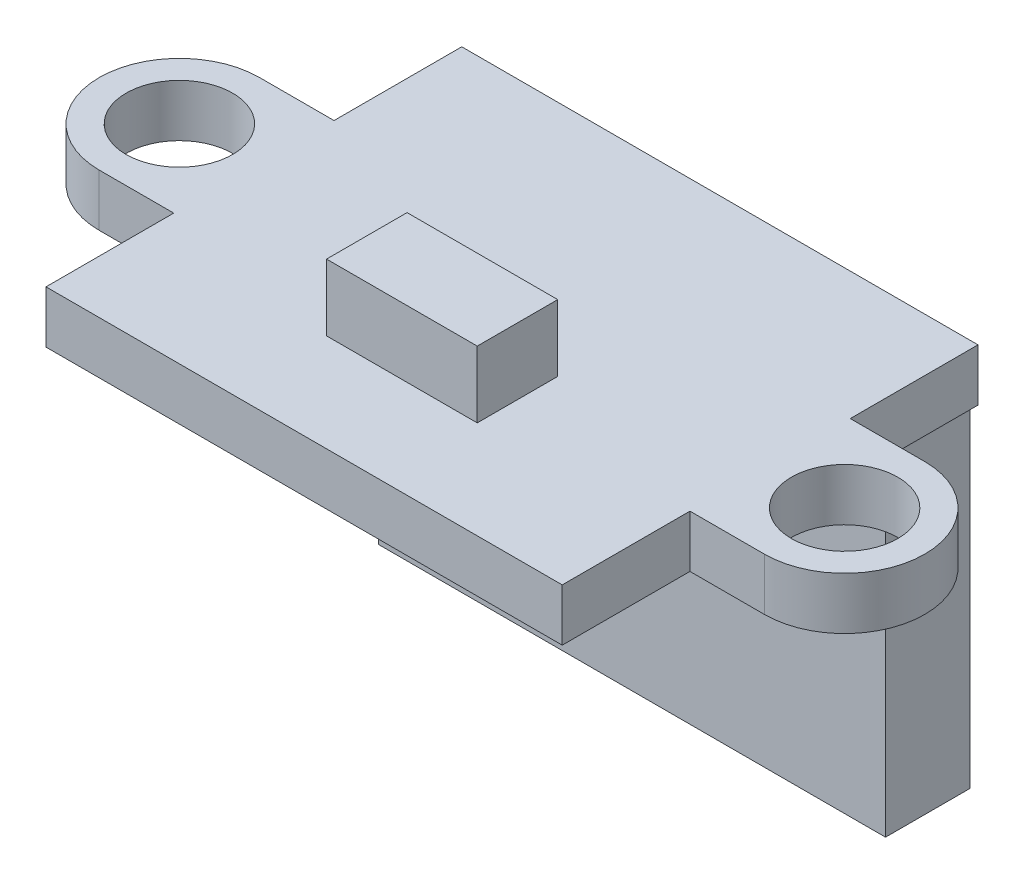
SolidWorks part; units mm, degrees
ref_plane "Front Plane" through (0, 0, 0) normal (0, 0, 1) x (1, 0, 0)
ref_plane "Top Plane" through (0, 0, 0) normal (0, 1, 0) x (1, 0, 0)
ref_plane "Right Plane" through (0, 0, 0) normal (1, 0, 0) x (0, 0, -1)
sketch "Sketch1" plane through (0, 0, 0) normal (0, 1, 0) x (1, 0, 0)
  line L1 (-7.76, -6.25) -> (7.76, -6.25)
  line L2 (-7.76, -6.25) -> (-7.76, -2.41)
  line L3 (-7.76, 6.25) -> (7.76, 6.25)
  line L4 (7.76, -6.25) -> (7.76, -2.41)
  line L5 (-7.76, -6.25) -> (7.76, 6.25) construction
  line L6 (-7.76, 6.25) -> (7.76, -6.25) construction
  line L7 (-10, -2.41) -> (-7.76, -2.41)
  line L8 (-10, -2.41) -> (-10, 2.41) construction
  line L9 (-10, 2.41) -> (-7.76, 2.41)
  line L10 (10, -2.41) -> (10, 2.41) construction
  line L11 (-10, -2.41) -> (10, 2.41) construction
  line L12 (-10, 2.41) -> (10, -2.41) construction
  line L13 (-7.76, 2.41) -> (-7.76, 6.25)
  line L14 (7.76, -2.41) -> (10, -2.41)
  line L15 (7.76, 2.41) -> (7.76, 6.25)
  line L16 (7.76, 2.41) -> (10, 2.41)
  arc A0 (-10, -2.41) -> (-10, 2.41) centre (-10, 0) cw
  arc A1 (10, 2.41) -> (10, -2.41) centre (10, 0) cw
  circle A2 centre (-10, 0) radius 1.6
  circle A3 centre (10, 0) radius 1.6
  point P0 (0, 0)
  point P6 (0, 0)
  dimension "D1" = 15.52
  dimension "D5" = 3.2
  dimension "D2" = 12.5
  dimension "D3" = 20
  dimension "D4" = 4.82
extrude "Boss-Extrude1" add sketch "Sketch1" along normal blind 1.57
sketch "Sketch2" plane through (0, 1.57, 0) normal (0, 1, 0) x (1, 0, 0)
  line L0 (0, 6.25) -> (0, -6.25) construction
  line L1 (7.76, 6.25) -> (-7.76, 6.25) construction
  line L2 (-7.76, -6.25) -> (7.76, -6.25) construction
  line L4 (-2.265, -3.31) -> (2.265, -3.31)
  line L5 (-2.265, -3.31) -> (-2.265, -0.89)
  line L6 (-2.265, -0.89) -> (2.265, -0.89)
  line L7 (2.265, -3.31) -> (2.265, -0.89)
  line L8 (-2.265, -3.31) -> (2.265, -0.89) construction
  line L9 (-2.265, -0.89) -> (2.265, -3.31) construction
  point P6 (0, -2.1)
  dimension "D1" = 4.53
  dimension "D2" = 2.42
  dimension "D3" = 5.36
extrude "Boss-Extrude2" add sketch "Sketch2" along normal blind 2
sketch "Sketch3" plane through (0, 0, 0) normal (0, -1, 0) x (1, 0, 0)
  line L0 (0, 6.25) -> (0, -6.25) construction
  line L1 (-7.76, 6.25) -> (7.76, 6.25) construction
  line L2 (7.76, -6.25) -> (-7.76, -6.25) construction
  line L4 (-7.62, -6.15) -> (7.62, -6.15)
  line L5 (-7.62, -6.15) -> (-7.62, -3.61)
  line L6 (-7.62, -3.61) -> (7.62, -3.61)
  line L7 (7.62, -6.15) -> (7.62, -3.61)
  line L8 (-7.62, -6.15) -> (7.62, -3.61) construction
  line L9 (-7.62, -3.61) -> (7.62, -6.15) construction
  point P6 (0, -4.88)
  dimension "D1" = 15.24
  dimension "D2" = 2.54
  dimension "D3" = 0.1
extrude "Boss-Extrude3" add sketch "Sketch3" along normal blind 10
